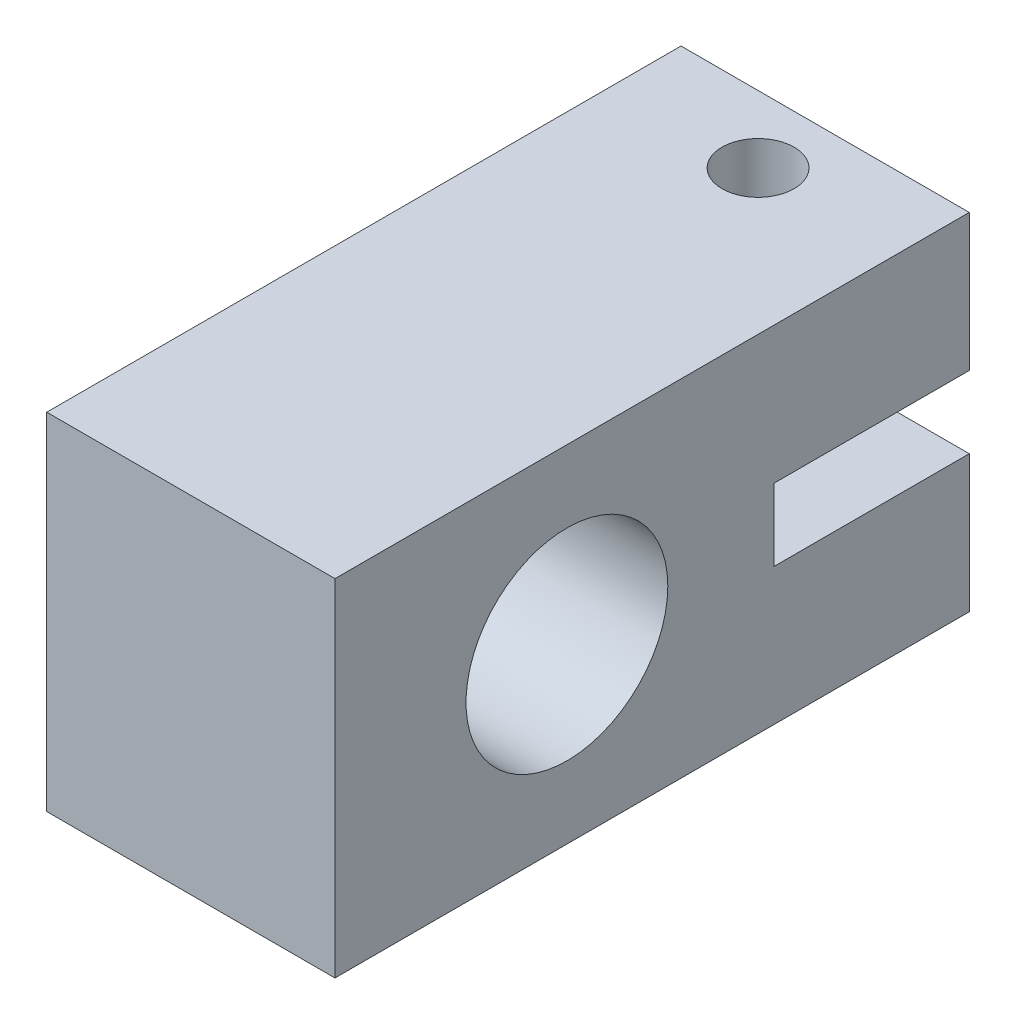
SolidWorks part; units mm, degrees
ref_plane "Спереди" through (0, 0, 0) normal (0, 0, 1) x (1, 0, 0)
ref_plane "Сверху" through (0, 0, 0) normal (0, 1, 0) x (1, 0, 0)
ref_plane "Справа" through (0, 0, 0) normal (1, 0, 0) x (0, 0, -1)
sketch "Эскиз1" plane through (0, 0, 0) normal (1, 0, 0) x (0, 0, -1)
  line L1 (-16.0934, 12) -> (27.9165, 12)
  line L2 (-16.0934, 12) -> (-16.0934, -12)
  line L3 (-16.0934, -12) -> (27.9165, -12)
  line L4 (27.9165, 12) -> (27.9165, 2.5)
  line L7 (27.9165, -2.5) -> (27.9165, -12)
  line L8 (14.3715, 2.5) -> (27.9165, 2.5)
  line L9 (14.3715, 2.5) -> (14.3715, -2.5)
  line L10 (14.3715, -2.5) -> (27.9165, -2.5)
  circle A0 centre (0, 0) radius 7
extrude "Вытянуть1" add sketch "Эскиз1" along normal blind 20
sketch "Эскиз2" plane through (0, 12, 0) normal (0, 1, 0) x (1, 0, 0)
  line L0 (10, 27.9165) -> (10, 19.5976) construction
  circle A0 centre (10, 23.2628) radius 2.5
extrude "Вытянуть2" cut sketch "Эскиз2" against normal through all
